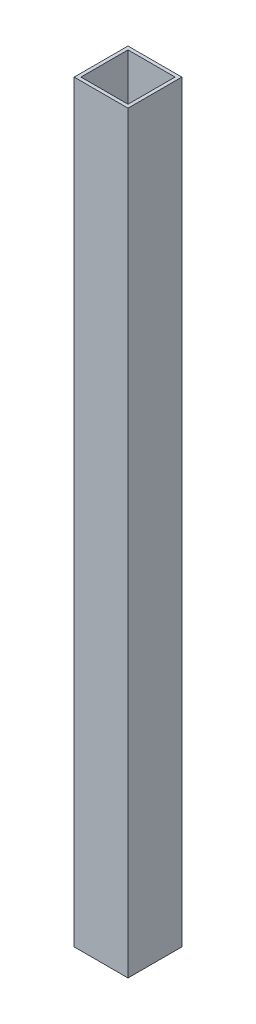
SolidWorks part; units mm, degrees
ref_plane "Front Plane" through (0, 0, 0) normal (0, 0, 1) x (1, 0, 0)
ref_plane "Top Plane" through (0, 0, 0) normal (0, 1, 0) x (1, 0, 0)
ref_plane "Right Plane" through (0, 0, 0) normal (1, 0, 0) x (0, 0, -1)
sketch "Sketch1" plane through (0, 0, 0) normal (0, 1, 0) x (1, 0, 0)
  line L1 (-12.7, -12.7) -> (12.7, -12.7)
  line L2 (-12.7, -12.7) -> (-12.7, 12.7)
  line L3 (-12.7, 12.7) -> (12.7, 12.7)
  line L4 (12.7, -12.7) -> (12.7, 12.7)
  line L5 (-12.7, -12.7) -> (12.7, 12.7) construction
  line L6 (-12.7, 12.7) -> (12.7, -12.7) construction
  line L7 (-11.1125, -11.1125) -> (11.1125, -11.1125)
  line L8 (-11.1125, -11.1125) -> (-11.1125, 11.1125)
  line L9 (-11.1125, 11.1125) -> (11.1125, 11.1125)
  line L10 (11.1125, -11.1125) -> (11.1125, 11.1125)
  line L11 (-11.1125, -11.1125) -> (11.1125, 11.1125) construction
  line L12 (-11.1125, 11.1125) -> (11.1125, -11.1125) construction
  point P0 (0, 0)
  point P6 (0, 0)
  dimension "D1" = 25.4
  dimension "D2" = 1.5875
extrude "Boss-Extrude1" add sketch "Sketch1" along normal blind 355.6
